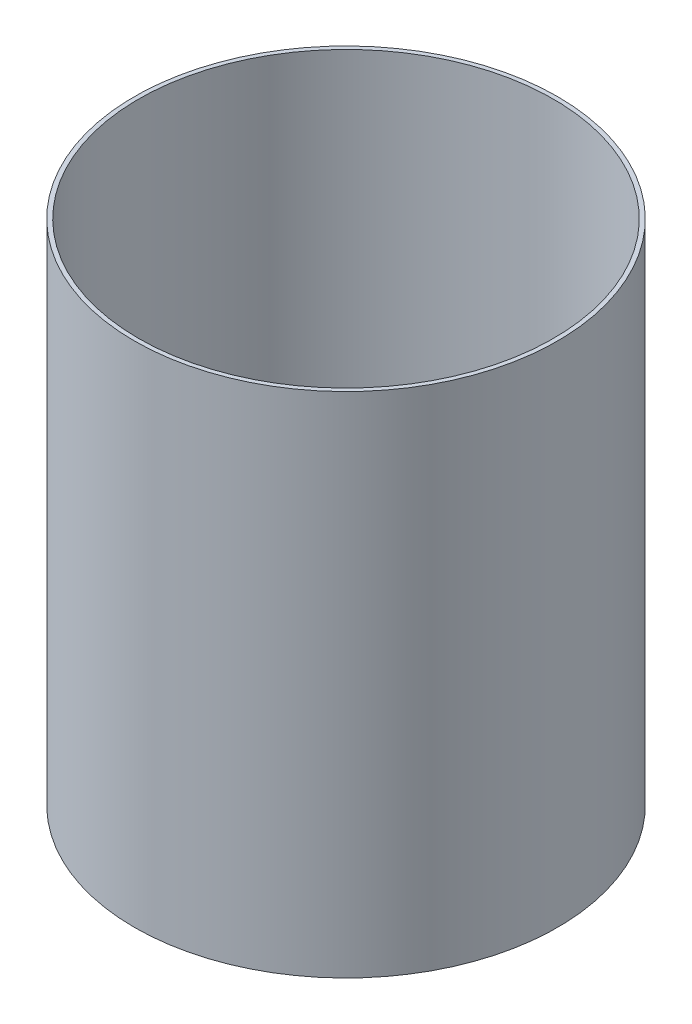
SolidWorks part; units mm, degrees
ref_plane "Front Plane" through (0, 0, 0) normal (0, 0, 1) x (1, 0, 0)
ref_plane "Top Plane" through (0, 0, 0) normal (0, 1, 0) x (1, 0, 0)
ref_plane "Right Plane" through (0, 0, 0) normal (1, 0, 0) x (0, 0, -1)
sketch "Sketch1" plane through (0, 0, 0) normal (0, 1, 0) x (1, 0, 0)
  circle A0 centre (0, 0) radius 100
  circle A1 centre (0, 0) radius 98
  dimension "D1" = 200
  dimension "D2" = 2
extrude "Boss-Extrude1" add sketch "Sketch1" along normal blind 240
